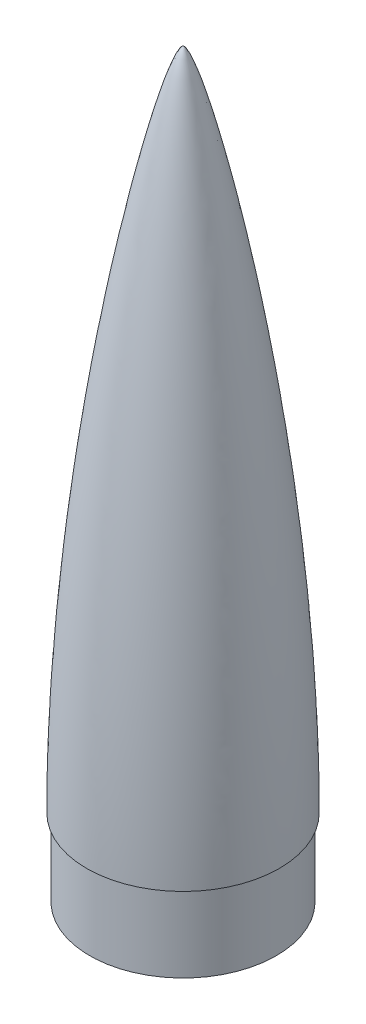
SolidWorks part; units mm, degrees
material "Plástico personalizado (1)"
ref_plane "Plano frontal" through (0, 0, 0) normal (0, 0, 1) x (1, 0, 0)
ref_plane "Plano superior" through (0, 0, 0) normal (0, 1, 0) x (1, 0, 0)
ref_plane "Plano direito" through (0, 0, 0) normal (1, 0, 0) x (0, 0, -1)
sketch "Esboço1" plane through (0, 0, 0) normal (0, 0, 1) x (1, 0, 0)
  line L0 (0, 0) -> (0, 250) construction
  line L3 (32.5, 115.6799) -> (32.5, -65.2833) construction
  line L4 (-61.4853, 250) -> (61.4853, 250) construction
  line L7 (31.5, 0) -> (31.5, 26)
  line L8 (31.5, 26) -> (32.5, 26)
  line L9 (30.25, 1.25) -> (30.25, 0)
  line L10 (30.25, 1.25) -> (30.25, 27.25)
  line L11 (30.25, 27.25) -> (31.0556, 27.25)
  line L13 (30.25, 0) -> (31.5, 0)
  line L14 (0, 1.25) -> (30.25, 1.25) construction
  line L15 (0, 0) -> (31.5, 0) construction
  line L17 (0, 250) -> (0, 217.363)
  line L18 (0, 217.363) -> (9.2518, 217.363)
  line L19 (32.5, 26) -> (0, 250) construction
  line L20 (31.0556, 27.25) -> (-1.237, 249.8205) construction
  spline S0 degree 3 poles (32.5, 26) (32.5, 136) (5, 250) (0, 250) knots 0 0 0 0 1 1 1 1
  spline S1 degree 3 poles (31.0556, 27.25) (32.5651, 97.0341) (16.8817, 189.3868) (9.2518, 217.363) knots 0 0 0 0 1 1 1 1
  point P15 (6.2513, 228.9097)
  point P19 (9.2518, 217.363)
  dimension "D4" = 15
  dimension "D5" = 330
  dimension "D1" = 250
  dimension "D2" = 31.5
  dimension "D3" = 1
  dimension "D6" = 26
  dimension "D7" = 1.25
revolve "Revolução1" add sketch "Esboço1" angle 360 about L0
